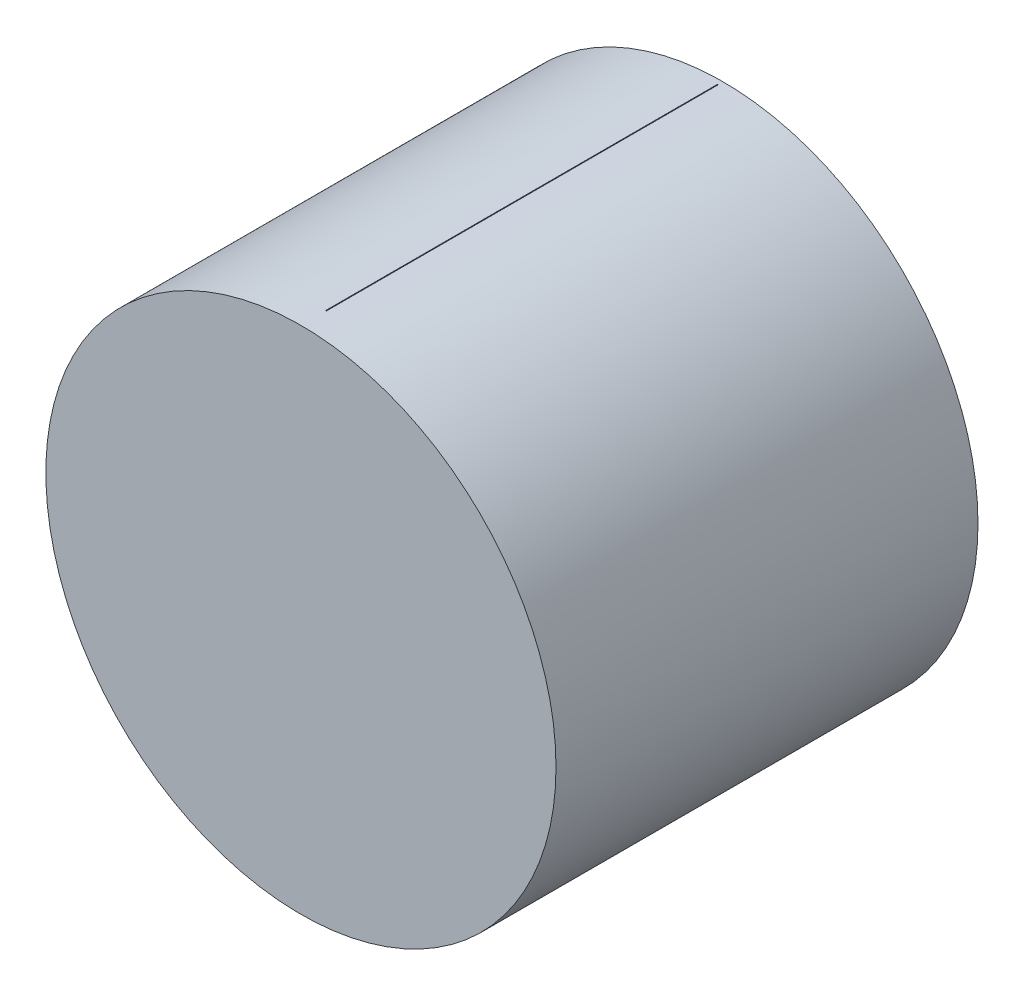
SolidWorks part; units mm, degrees
ref_plane "Спереди" through (0, 0, 0) normal (0, 0, 1) x (1, 0, 0)
ref_plane "Сверху" through (0, 0, 0) normal (0, 1, 0) x (1, 0, 0)
ref_plane "Справа" through (0, 0, 0) normal (1, 0, 0) x (0, 0, -1)
sketch "Эскиз1" plane through (0, 0, 0) normal (0, 0, 1) x (1, 0, 0)
  circle A0 centre (0, 0) radius 14.925
  dimension "D1" = 29.85
extrude "Бобышка-Вытянуть1" add sketch "Эскиз1" along normal blind 2
sketch "Эскиз2" plane through (0, 0, 2) normal (0, 0, 1) x (1, 0, 0)
  circle A0 centre (0, 0) radius 14.925
  circle A1 centre (0, 0) radius 16.925
  dimension "D1" = 2
extrude "Бобышка-Вытянуть2" add sketch "Эскиз2" against normal blind 28
sketch "Эскиз3" plane through (-4.3999, 4.2404, -22) normal (0, 1, 0) x (1, 0, 0)
  line L0 (4.4209, 3.6704) -> (4.3709, 3.6704)
  line L1 (4.4209, 3.6704) -> (4.4209, -22.3296)
  line L2 (4.4209, -22.3296) -> (4.3709, -22.3296)
  line L3 (4.3709, 3.6704) -> (4.3709, -22.3296)
extrude "Вырез-Вытянуть1" cut sketch "Эскиз3" along normal blind 27
